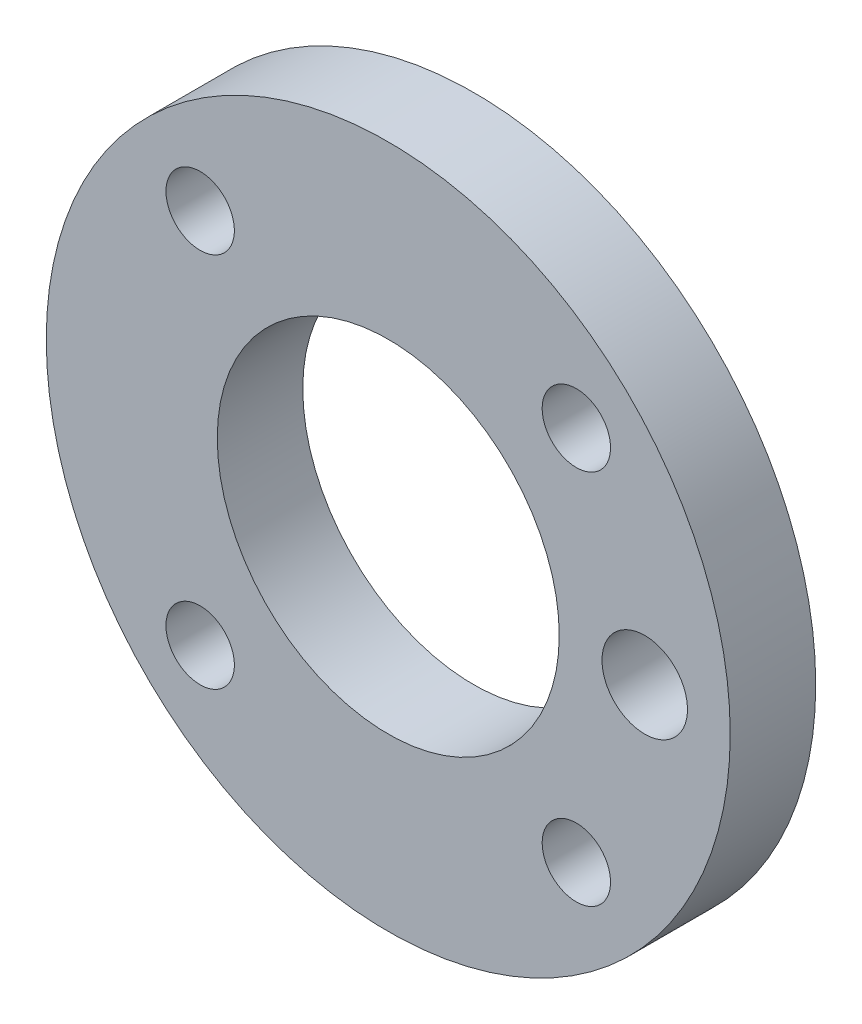
SolidWorks part; units mm, degrees
ref_plane "Front Plane" through (0, 0, 0) normal (0, 0, 1) x (1, 0, 0)
ref_plane "Top Plane" through (0, 0, 0) normal (0, 1, 0) x (1, 0, 0)
ref_plane "Right Plane" through (0, 0, 0) normal (1, 0, 0) x (0, 0, -1)
sketch "Sketch1" plane through (0, 0, 0) normal (1, 0, 0) x (0, 0, -1)
  line L1 (11, 11) -> (-11, 11) construction
  line L2 (11, 11) -> (11, -11) construction
  line L3 (11, -11) -> (-11, -11) construction
  line L4 (-11, 11) -> (-11, -11) construction
  line L5 (11, 11) -> (-11, -11) construction
  line L6 (11, -11) -> (-11, 11) construction
  circle A0 centre (0, 0) radius 20
  circle A1 centre (0, 0) radius 10
  circle A2 centre (-11, 11) radius 2
  circle A3 centre (11, 11) radius 2
  circle A4 centre (11, -11) radius 2
  circle A5 centre (-11, -11) radius 2
  circle A6 centre (-15, 0) radius 2.5
  dimension "D1" = 40
  dimension "D2" = 20
  dimension "D5" = 4
  dimension "D8" = 5
  dimension "D3" = 22
  dimension "D4" = 22
  dimension "D9" = 15
  dimension "D6" = 2
  dimension "D7" = 2
extrude "Boss-Extrude1" add sketch "Sketch1" along normal blind 5
move or copy body "Body-Move/Copy1" bodies to move or copy 101 copy no rotation origin (0, 0, 0) rotation axis (0.7071, 0, 0.7071) rotation angle 180
